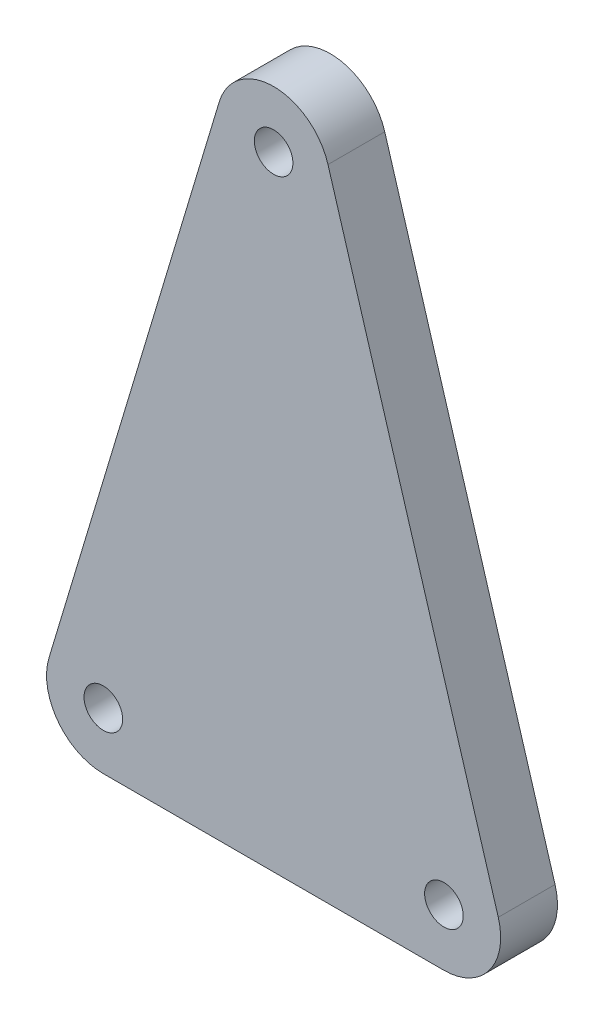
SolidWorks part; units mm, degrees
ref_plane "Front Plane" through (0, 0, 0) normal (0, 0, 1) x (1, 0, 0)
ref_plane "Top Plane" through (0, 0, 0) normal (0, 1, 0) x (1, 0, 0)
ref_plane "Right Plane" through (0, 0, 0) normal (1, 0, 0) x (0, 0, -1)
sketch "Sketch1" plane through (0, 0, 0) normal (0, 0, 1) x (1, 0, 0)
  line L0 (0, 0) -> (15, 0) construction
  line L1 (0, 0) -> (0, 49.92) construction
  line L2 (4.7885, 51.3589) -> (19.7885, 1.4389)
  line L3 (15, -5) -> (-15, -5)
  line L4 (0, 49.92) -> (0, 53.84) construction
  line L5 (-4.7885, 51.3589) -> (-19.7885, 1.4389)
  circle A0 centre (0, 49.92) radius 1.7 construction
  circle A1 centre (15, 0) radius 1.7 construction
  arc A2 (15, -5) -> (19.7885, 1.4389) centre (15, 0) ccw
  arc A3 (4.7885, 51.3589) -> (-4.7885, 51.3589) centre (0, 49.92) ccw
  circle A4 centre (-15, 0) radius 1.7 construction
  arc A5 (-15, -5) -> (-19.7885, 1.4389) centre (-15, 0) cw
  point P16 (0, -5)
  dimension "D1" = 3.4
  dimension "D2" = 10
  dimension "D3" = 15
  dimension "D4" = 49.92
extrude "Boss-Extrude1" add sketch "Sketch1" along normal blind 5
hole_wizard "CSK for M3 Flat Head Machine Screw2" positions "3DSketch2" profile "Sketch4" countersink size "M3" standard "ANSI Metric" end condition through all
sketch3d "3DSketch2"
  point P0 (0, 49.92, 0)
  point P3 (15, 0, 0)
  point P6 (-15, 0, 0)
  point P10 (0, 49.92, 0)
  point P12 (15, 0, 0)
  point P14 (-15, 0, 0)
sketch "Sketch4" plane through (-15, 0, 0) normal (1, 0, 0) x (0, 1, 0)
  line L0 (0, 0) -> (0, 5)
  line L1 (0, 5) -> (1.7, 5)
  line L2 (1.7, 5) -> (1.7, 1.45)
  line L3 (1.7, 1.45) -> (3.15, 0)
  line L5 (3.15, 0) -> (0, 0)
  line L6 (-1.7, 1.45) -> (-3.15, 0) construction
  line L11 (0, -6.35) -> (0, 107.95) construction
  dimension "Thru Hole Dia." = 3.4
  dimension "Thru Hole Depth" = 5
  dimension "Near C'Sink Dia." = 6.3
  dimension "Near C'Sink Angle" = 90
